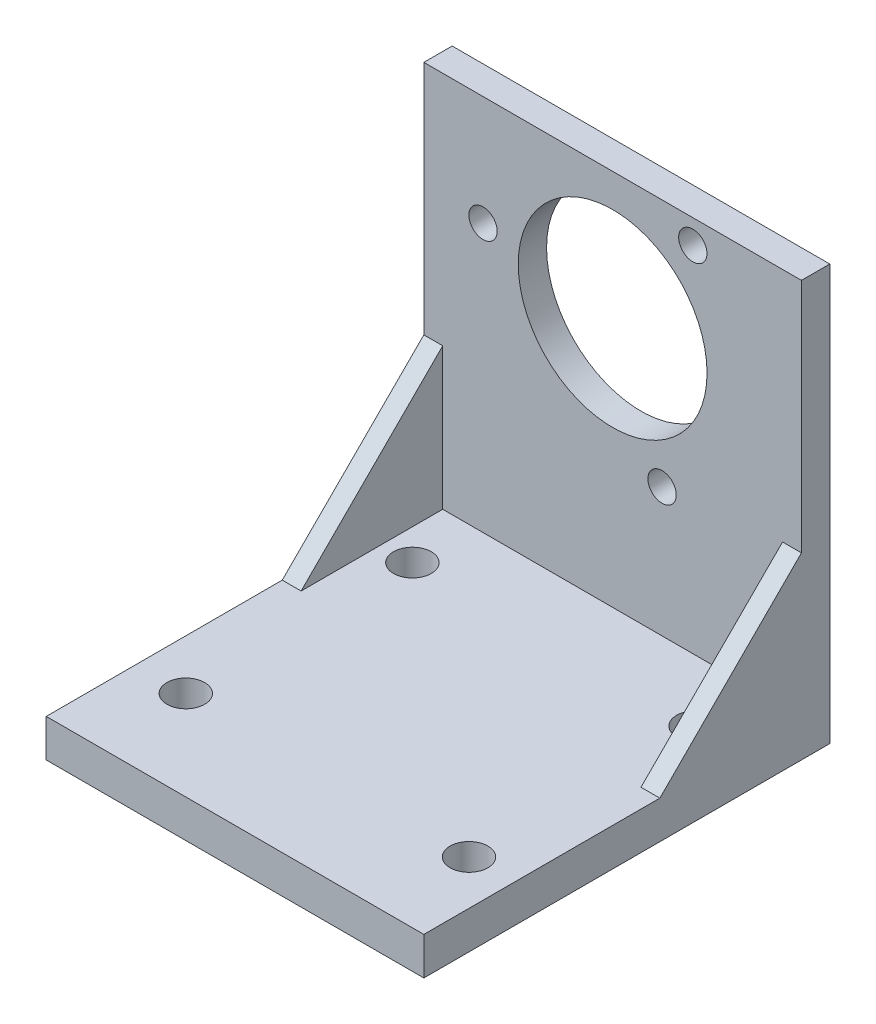
SolidWorks part; units mm, degrees
ref_plane "Front Plane" through (0, 0, 0) normal (0, 0, 1) x (1, 0, 0)
ref_plane "Top Plane" through (0, 0, 0) normal (0, 1, 0) x (1, 0, 0)
ref_plane "Right Plane" through (0, 0, 0) normal (1, 0, 0) x (0, 0, -1)
sketch "Sketch1" plane through (0, 0, 0) normal (0, 1, 0) x (1, 0, 0)
  line L0 (-20, 18.5) -> (20, 18.5)
  line L1 (-20, -21.5) -> (20, -21.5)
  line L2 (-20, -21.5) -> (-20, 21.5)
  line L3 (-20, 21.5) -> (20, 21.5)
  line L4 (20, -21.5) -> (20, 21.5)
  line L5 (-20, -21.5) -> (20, 21.5) construction
  line L6 (-20, 21.5) -> (20, -21.5) construction
  circle A7 centre (-14.7151, 12) radius 2
  circle A8 centre (15.2849, 12) radius 2
  circle A9 centre (-14.7151, -12) radius 2
  circle A10 centre (15.2849, -12) radius 2
  point P0 (0, 0)
  dimension "D4" = 30
  dimension "D5" = 4
  dimension "D6" = 4
  dimension "D7" = 24
  dimension "D8" = 9.5
  dimension "D9" = 5.2849
  dimension "D10" = 4
  dimension "D12" = 4
  dimension "D2" = 40
  dimension "D3" = 43
  dimension "D11" = 9.5
  dimension "D13" = 3
extrude "Boss-Extrude1" add sketch "Sketch1" against normal blind 4
sketch "Sketch4" plane through (0, 0, 0) normal (0, 1, 0) x (1, 0, 0)
  line L1 (-20, -21.5) -> (-20, 21.5) construction
  line L2 (20, -21.5) -> (20, 21.5) construction
  line L5 (-20, 21.5) -> (20, 21.5)
  line L6 (-20, 21.5) -> (-20, 18.5)
  line L7 (-20, 18.5) -> (20, 18.5)
  line L8 (-20, -21.5) -> (20, -21.5)
  line L9 (20, -21.5) -> (20, 21.5)
  line L10 (20, 21.5) -> (-20, 21.5)
  line L11 (-20, 21.5) -> (-20, -21.5)
  line L12 (-20, -21.5) -> (20, -21.5)
  line L13 (20, -21.5) -> (20, 12.2)
  line L15 (-20, 12.2) -> (-20, -21.5)
  line L16 (20, 21.5) -> (20, 18.5)
  line M13 (20, -21.5) -> (20, 21.5)
  line M14 (20, 21.5) -> (-20, 21.5)
  line M15 (-20, 21.5) -> (-20, -21.5)
  dimension "D1" = 3
  dimension "D2" = 0
extrude "Boss-Extrude2" add sketch "Sketch4" along normal blind 40 contours L7 M15 M13 M14
sketch "Sketch5" plane through (0, 0, -18.5) normal (0, 0, 1) x (1, 0, 0)
  line L0 (-20, 40) -> (20, -4) construction
  line L1 (-20, -4) -> (20, 40) construction
  line L2 (0, 26.5) -> (0, 40) construction
  line L5 (-20, 40) -> (20, 40) construction
  circle A0 centre (0, 26.5) radius 13.8564
  circle A2 centre (8.492, 37.4493) radius 1.5
  circle A3 centre (-13.7283, 28.3796) radius 1.5
  circle A4 centre (5.2364, 13.6711) radius 1.5
  circle A5 centre (0, 26.5) radius 10
  point P13 (0, 26.5)
  point P18 (0, 19.5)
  dimension "D2" = 24
  dimension "D3" = 24
  dimension "D4" = 13.5
  dimension "D1" = 24
extrude "Cut-Extrude1" cut sketch "Sketch5" against normal blind 24 contours A5 | A0 A3 | A0 A3 | A0 A4 | A0 A2 | A0 A2
sketch "Sketch6" plane through (20, 0, 0) normal (1, 0, 0) x (0, 0, -1)
  line L0 (18.5, 15) -> (3.5, 0)
  line L1 (18.5, 40) -> (18.5, 0) construction
  line L2 (21.5, 0) -> (-21.5, 0) construction
  line L3 (3.5, 0) -> (18.5, 0)
  line L4 (18.5, 0) -> (18.5, 15)
  dimension "D1" = 15
  dimension "D2" = 15
extrude "Boss-Extrude3" add sketch "Sketch6" against normal blind 2
sketch "Sketch7" plane through (-20, 0, 0) normal (-1, 0, 0) x (0, 0, 1)
  line L0 (-18.5, 15) -> (-3.5, 0)
  line L1 (-3.5, 0) -> (-18.5, 0)
  line L2 (-18.5, 0) -> (-18.5, 15)
extrude "Boss-Extrude4" add sketch "Sketch7" against normal blind 2
